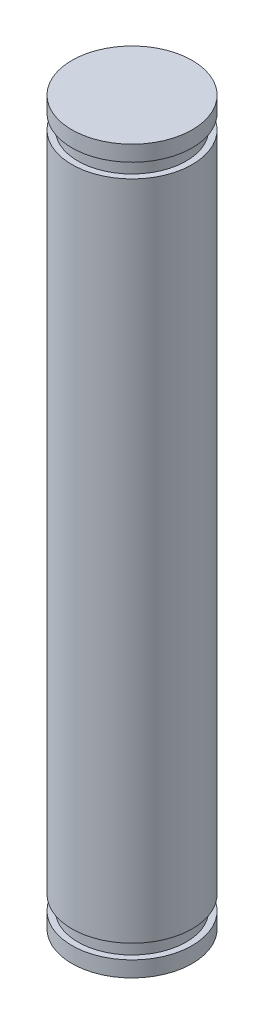
SolidWorks part; units mm, degrees
ref_plane "前视基准面" through (0, 0, 0) normal (0, 0, 1) x (1, 0, 0)
ref_plane "上视基准面" through (0, 0, 0) normal (0, 1, 0) x (1, 0, 0)
ref_plane "右视基准面" through (0, 0, 0) normal (1, 0, 0) x (0, 0, -1)
sketch "草图1" plane through (0, 0, 0) normal (0, 0, 1) x (1, 0, 0)
  line L12 (-6.9556, 16.1149) -> (-11.9556, 16.1149)
  line L13 (-11.9556, 16.1149) -> (-11.9556, 76.1149) construction
  line L14 (-6.9556, 16.1149) -> (-6.9556, 17.4149)
  line L15 (-6.9556, 17.4149) -> (-7.4556, 17.4149)
  line L16 (-7.4556, 17.4149) -> (-7.4556, 18.6149)
  line L17 (-7.4556, 18.6149) -> (-6.9556, 18.6149)
  line L18 (-6.9556, 18.6149) -> (-6.9556, 73.6149)
  line L19 (-6.9556, 73.6149) -> (-7.4556, 73.6149)
  line L20 (-7.4556, 73.6149) -> (-7.4556, 74.8149)
  line L21 (-7.4556, 74.8149) -> (-6.9556, 74.8149)
  line L22 (-6.9556, 74.8149) -> (-6.9556, 76.1149)
  line L23 (-6.9556, 76.1149) -> (-11.9556, 76.1149)
  line L24 (-11.9556, 16.1149) -> (-11.9556, 76.1149)
  dimension "D1" = 60
  dimension "D2" = 55
  dimension "D3" = 5
  dimension "D4" = 1.2
  dimension "D5" = 1.2
  dimension "D6" = 0.5
revolve "旋转1" add sketch "草图1" angle 360 about L13
